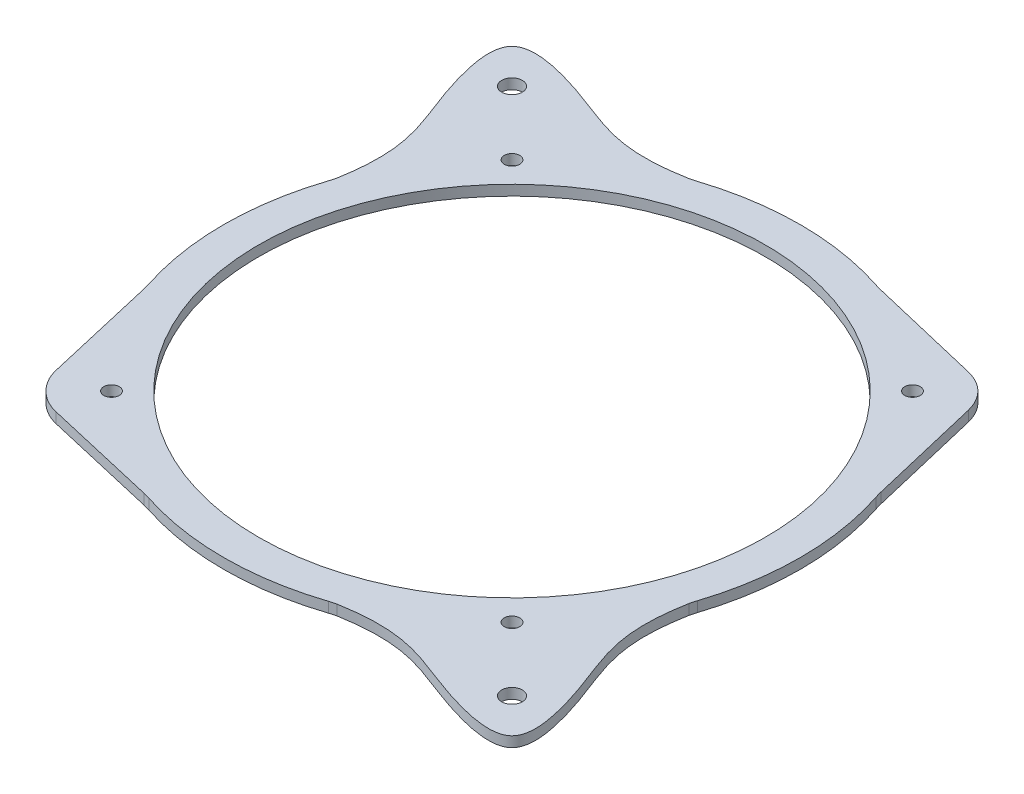
SolidWorks part; units mm, degrees
material "6061-T6 (SS)"
ref_plane "Front Plane" through (0, 0, 0) normal (0, 0, 1) x (1, 0, 0)
ref_plane "Top Plane" through (0, 0, 0) normal (0, 1, 0) x (1, 0, 0)
ref_plane "Right Plane" through (0, 0, 0) normal (1, 0, 0) x (0, 0, -1)
sketch "Sketch1" plane through (0, 0, 0) normal (0, 1, 0) x (1, 0, 0)
  line L0 (49.872, -261.8935) -> (473.872, -261.8935) construction
  line L1 (17.8971, 48.9297) -> (40.1493, 43.6512) construction
  line L2 (43.8664, 39.9141) -> (49.0252, 17.6338) construction
  line L3 (48.9297, -17.8971) -> (43.6512, -40.1493) construction
  line L4 (39.9141, -43.8664) -> (17.6338, -49.0252) construction
  line L5 (-17.8971, -48.9297) -> (-40.1493, -43.6512) construction
  line L6 (-43.8664, -39.9141) -> (-49.0252, -17.6338) construction
  line L7 (-48.9297, 17.8971) -> (-43.6512, 40.1493) construction
  line L8 (-39.9141, 43.8664) -> (-17.6338, 49.0252) construction
  line L9 (0, 38.8907) -> (0, -38.8907) construction
  line L10 (-38.8907, 0) -> (38.8907, 0) construction
  line L11 (-44.8768, 65.2993) -> (-22.6789, 70.4391) construction
  line L12 (-38.8907, 38.8907) -> (38.8907, 38.8907) construction
  line L13 (-38.8907, 38.8907) -> (-38.8907, -38.8907) construction
  line L14 (-38.8907, -38.8907) -> (38.8907, -38.8907) construction
  line L15 (38.8907, 38.8907) -> (38.8907, -38.8907) construction
  line L16 (23.0572, 70.3162) -> (45.2271, 65.0572) construction
  line L17 (65.2993, 44.8768) -> (70.4391, 22.6789) construction
  line L18 (70.3162, -23.0572) -> (65.0572, -45.2271) construction
  line L19 (-48.1292, 57.9935) -> (-53.0614, 53.0614) construction
  line L20 (44.8768, -65.2993) -> (22.6789, -70.4391) construction
  line L21 (-23.0572, -70.3162) -> (-45.2271, -65.0572) construction
  line L22 (-65.2993, -44.8768) -> (-70.4391, -22.6789) construction
  line L23 (-70.3162, 23.0572) -> (-65.0572, 45.2271) construction
  line L25 (18.8203, 52.8217) -> (41.0725, 47.5432)
  line L30 (-47.7633, -40.8164) -> (-52.9221, -18.5361)
  line L32 (-57.9823, 57.9823) -> (-38.8907, 38.8907) construction
  line L33 (-38.8907, 38.8907) -> (38.8907, -38.8907) construction
  line L34 (38.8907, -38.8907) -> (57.9823, -57.9823) construction
  line L35 (38.8907, 38.8907) -> (57.9823, 57.9823) construction
  line L36 (-38.8907, -38.8907) -> (-57.9823, -57.9823) construction
  line L37 (-38.8907, -38.8907) -> (38.8907, 38.8907) construction
  line L38 (-53.0614, 53.0614) -> (-57.9935, 48.1292) construction
  line L39 (-39.6632, 55.1015) -> (-47.3824, 47.3824) construction
  line L40 (-47.3824, 47.3824) -> (-55.1015, 39.6632) construction
  line L41 (52.8217, 18.8203) -> (47.5432, 41.0725)
  line L42 (-40.8164, 47.7633) -> (-18.5361, 52.9221) construction
  line L43 (-52.8217, 18.8203) -> (-47.5432, 41.0725) construction
  line L44 (47.7633, 40.8164) -> (52.9221, 18.5361) construction
  line L45 (52.8217, -18.8203) -> (47.5432, -41.0725) construction
  line L46 (40.8164, -47.7633) -> (18.5361, -52.9221) construction
  line L47 (-18.8203, -52.8217) -> (-41.0725, -47.5432) construction
  line L48 (-40.8164, -47.7633) -> (-18.5361, -52.9221)
  arc A1 (-17.6338, 49.0252) -> (-15.9939, 49.4792) centre (-22.1454, 68.5097) ccw construction
  arc A2 (0.1397, 51.9998) -> (-15.9939, 49.4792) centre (0, 0) ccw construction
  arc A3 (16.2596, 49.3926) -> (0.1397, 51.9998) centre (0, 0) ccw construction
  arc A4 (16.2596, 49.3926) -> (17.8971, 48.9297) centre (22.5132, 68.3897) ccw construction
  arc A5 (43.8664, 39.9141) -> (40.1493, 43.6512) centre (38.9952, 38.7862) ccw construction
  arc A6 (49.0252, 17.6338) -> (49.4792, 15.9939) centre (68.5097, 22.1454) ccw construction
  arc A7 (49.3926, -16.2596) -> (49.4792, 15.9939) centre (0, 0) ccw construction
  arc A8 (49.3926, -16.2596) -> (48.9297, -17.8971) centre (68.3897, -22.5132) ccw construction
  arc A9 (39.9141, -43.8664) -> (43.6512, -40.1493) centre (38.7862, -38.9952) ccw construction
  arc A10 (17.6338, -49.0252) -> (15.9939, -49.4792) centre (22.1454, -68.5097) ccw construction
  arc A11 (-16.2596, -49.3926) -> (15.9939, -49.4792) centre (0, 0) ccw construction
  arc A12 (-16.2596, -49.3926) -> (-17.8971, -48.9297) centre (-22.5132, -68.3897) ccw construction
  arc A13 (-43.8664, -39.9141) -> (-40.1493, -43.6512) centre (-38.9952, -38.7862) ccw construction
  arc A14 (-49.0252, -17.6338) -> (-49.4792, -15.9939) centre (-68.5097, -22.1454) ccw construction
  arc A15 (-49.3926, 16.2596) -> (-49.4792, -15.9939) centre (0, 0) ccw construction
  arc A16 (-49.3926, 16.2596) -> (-48.9297, 17.8971) centre (-68.3897, 22.5132) ccw construction
  arc A17 (-39.9141, 43.8664) -> (-43.6512, 40.1493) centre (-38.7862, 38.9952) ccw construction
  circle A18 centre (-38.8907, 38.8907) radius 1.5
  circle A19 centre (38.8907, 38.8907) radius 1.5
  circle A20 centre (38.8907, -38.8907) radius 1.5
  circle A21 centre (-38.8907, -38.8907) radius 1.5
  circle A22 centre (0, 0) radius 49.2
  arc A23 (-22.6789, 70.4391) -> (-22.6789, 70.4391) centre (-22.6789, 70.4391) ccw construction
  arc A24 (0.1989, 73.9997) -> (-22.6789, 70.4391) centre (0, 0) ccw construction
  arc A25 (23.0572, 70.3162) -> (0.1989, 73.9997) centre (0, 0) ccw construction
  arc A26 (23.0572, 70.3162) -> (23.0572, 70.3162) centre (23.0572, 70.3162) ccw construction
  arc A27 (65.2993, 44.8768) -> (45.2271, 65.0572) centre (38.9952, 38.7862) ccw construction
  arc A28 (70.4391, 22.6789) -> (70.4391, 22.6789) centre (70.4391, 22.6789) ccw construction
  arc A29 (70.3162, -23.0572) -> (70.4391, 22.6789) centre (0, 0) ccw construction
  arc A30 (70.3162, -23.0572) -> (70.3162, -23.0572) centre (70.3162, -23.0572) ccw construction
  arc A31 (44.8768, -65.2993) -> (65.0572, -45.2271) centre (38.7862, -38.9952) ccw construction
  arc A32 (22.6789, -70.4391) -> (22.6789, -70.4391) centre (22.6789, -70.4391) ccw construction
  arc A33 (-23.0572, -70.3162) -> (22.6789, -70.4391) centre (0, 0) ccw construction
  arc A34 (-23.0572, -70.3162) -> (-23.0572, -70.3162) centre (-23.0572, -70.3162) ccw construction
  arc A35 (-65.2993, -44.8768) -> (-45.2271, -65.0572) centre (-38.9952, -38.7862) ccw construction
  arc A36 (-70.4391, -22.6789) -> (-70.4391, -22.6789) centre (-70.4391, -22.6789) ccw construction
  arc A37 (-70.3162, 23.0572) -> (-70.4391, -22.6789) centre (0, 0) ccw construction
  arc A38 (-70.3162, 23.0572) -> (-70.3162, 23.0572) centre (-70.3162, 23.0572) ccw construction
  arc A39 (-44.8768, 65.2993) -> (-65.0572, 45.2271) centre (-38.7862, 38.9952) ccw construction
  arc A41 (0.1505, 55.9998) -> (-17.2242, 53.2853) centre (0, 0) ccw
  arc A42 (17.5103, 53.192) -> (0.1505, 55.9998) centre (0, 0) ccw
  arc A43 (17.5103, 53.192) -> (18.8203, 52.8217) centre (22.5132, 68.3897) ccw
  arc A44 (45.2538, 45.2538) -> (41.0725, 47.5432) centre (38.9952, 38.7862) ccw
  arc A52 (-47.7633, -40.8164) -> (-45.2538, -45.2538) centre (-38.9952, -38.7862) ccw
  arc A53 (-52.9221, -18.5361) -> (-53.2853, -17.2242) centre (-68.5097, -22.1454) ccw
  arc A54 (-53.192, 17.5103) -> (-53.2853, -17.2242) centre (0, 0) ccw
  arc A55 (-53.192, 17.5103) -> (-52.8217, 18.8203) centre (-68.3897, 22.5132) ccw
  arc A57 (-40.8164, 47.7633) -> (-47.5432, 41.0725) centre (-38.7862, 38.9952) ccw construction
  arc A58 (47.7633, 40.8164) -> (41.0725, 47.5432) centre (38.9952, 38.7862) ccw construction
  arc A59 (53.192, -17.5103) -> (53.2853, 17.2242) centre (0, 0) ccw construction
  arc A60 (52.9221, 18.5361) -> (53.2853, 17.2242) centre (68.5097, 22.1454) ccw construction
  arc A61 (53.192, -17.5103) -> (52.8217, -18.8203) centre (68.3897, -22.5132) ccw construction
  arc A62 (40.8164, -47.7633) -> (47.5432, -41.0725) centre (38.7862, -38.9952) ccw construction
  arc A63 (18.5361, -52.9221) -> (17.2242, -53.2853) centre (22.1454, -68.5097) ccw construction
  arc A64 (-17.5103, -53.192) -> (17.2242, -53.2853) centre (0, 0) ccw construction
  arc A65 (-17.5103, -53.192) -> (-18.8203, -52.8217) centre (-22.5132, -68.3897) ccw construction
  arc A66 (-47.7633, -40.8164) -> (-41.0725, -47.5432) centre (-38.9952, -38.7862) ccw construction
  arc A67 (45.2538, 45.2538) -> (47.5432, 41.0725) centre (38.7862, 38.9952) cw
  arc A68 (53.192, 17.5103) -> (52.8217, 18.8203) centre (68.3897, 22.5132) cw
  arc A69 (53.192, 17.5103) -> (55.9998, 0.1505) centre (0, 0) cw
  arc A70 (55.9998, 0.1505) -> (53.2853, -17.2242) centre (0, 0) cw
  arc A71 (52.9221, -18.5361) -> (53.2853, -17.2242) centre (68.5097, -22.1454) cw
  arc A72 (-40.8164, -47.7633) -> (-45.2538, -45.2538) centre (-38.7862, -38.9952) cw
  arc A73 (-18.5361, -52.9221) -> (-17.2242, -53.2853) centre (-22.1454, -68.5097) cw
  arc A74 (17.5103, -53.192) -> (-17.2242, -53.2853) centre (0, 0) cw
  arc A75 (17.5103, -53.192) -> (18.8203, -52.8217) centre (22.5132, -68.3897) cw
  arc A76 (-18.5361, 52.9221) -> (-17.2242, 53.2853) centre (-22.1454, 68.5097) ccw construction
  spline S0 degree 1 poles (-17.2242, 53.2853) (-18.5361, 52.9221) knots 0 0 1 1
  spline S1 degree 3 poles (-18.5361, 52.9221) (-33.0898, 50.2752) (-38.2524, 56.5088) (-60.5913, 60.5915) (-56.5308, 38.3726) (-50.3628, 33.1719) (-52.8217, 18.8203) knots 0 0 0 0 0.37824 0.501704 0.625168 1 1 1 1
  spline S2 degree 3 poles (52.9221, -18.5361) (50.2752, -33.0898) (56.5088, -38.2524) (60.5915, -60.5913) (38.3726, -56.5308) (33.1719, -50.3628) (18.8203, -52.8217) knots 0 0 0 0 0.37824 0.501704 0.625168 1 1 1 1
  point P22 (0, 0)
  point P65 (0, 0)
  point P66 (0, 0)
  point P69 (0, 0)
  point P70 (0, 0)
  dimension "D1" = 3
  dimension "D2" = 22
  dimension "D3" = 98.4
  dimension "D4" = 4
extrude "Boss-Extrude1" add sketch "Sketch1" along normal blind 2
sketch "Sketch2" plane through (0, 2, 0) normal (0, 1, 0) x (1, 0, 0)
  line L0 (-38.8907, 38.8907) -> (38.8907, 38.8907) construction
  line L1 (38.8907, 38.8907) -> (38.8907, -38.8907) construction
  line L2 (38.8907, -38.8907) -> (-38.8907, 38.8907) construction
  line L3 (-38.8907, 38.8907) -> (-38.8907, -38.8907) construction
  line L4 (-38.8907, -38.8907) -> (38.8907, -38.8907) construction
  line L5 (-38.8907, -38.8907) -> (38.8907, 38.8907) construction
  line L6 (-38.8907, 38.8907) -> (-57.9823, 57.9823) construction
  circle A0 centre (-51.2652, 51.2652) radius 2
  circle A1 centre (51.2652, -51.2652) radius 2
  spline S0 degree 3 poles (-18.5361, 52.9221) (-33.0898, 50.2752) (-38.2524, 56.5088) (-60.5913, 60.5915) (-56.5308, 38.3726) (-50.3628, 33.1719) (-52.8217, 18.8203) knots 0 0 0 0 0.37824 0.501704 0.625168 1 1 1 1 construction
  dimension "D1" = 4
  dimension "D2" = 145
extrude "Cut-Extrude1" cut sketch "Sketch2" against normal through all
